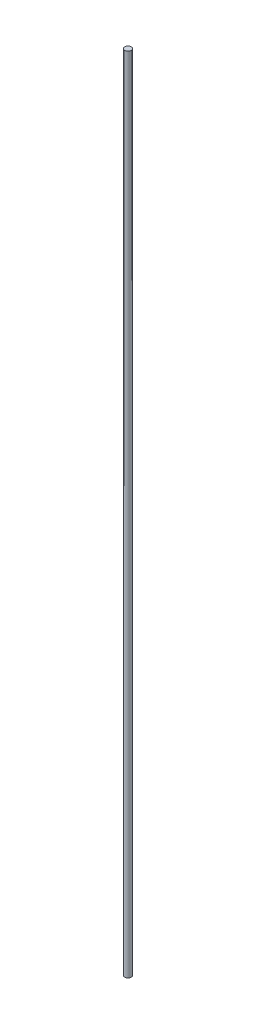
SolidWorks part; units mm, degrees
ref_plane "Front Plane" through (0, 0, 0) normal (0, 0, 1) x (1, 0, 0)
ref_plane "Top Plane" through (0, 0, 0) normal (0, 1, 0) x (1, 0, 0)
ref_plane "Right Plane" through (0, 0, 0) normal (1, 0, 0) x (0, 0, -1)
sketch "Sketch1" plane through (0, 0, 0) normal (0, 1, 0) x (1, 0, 0)
  circle A0 centre (0, 0) radius 4
  dimension "D1" = 8
extrude "Boss-Extrude1" add sketch "Sketch1" along normal mid plane 1000
